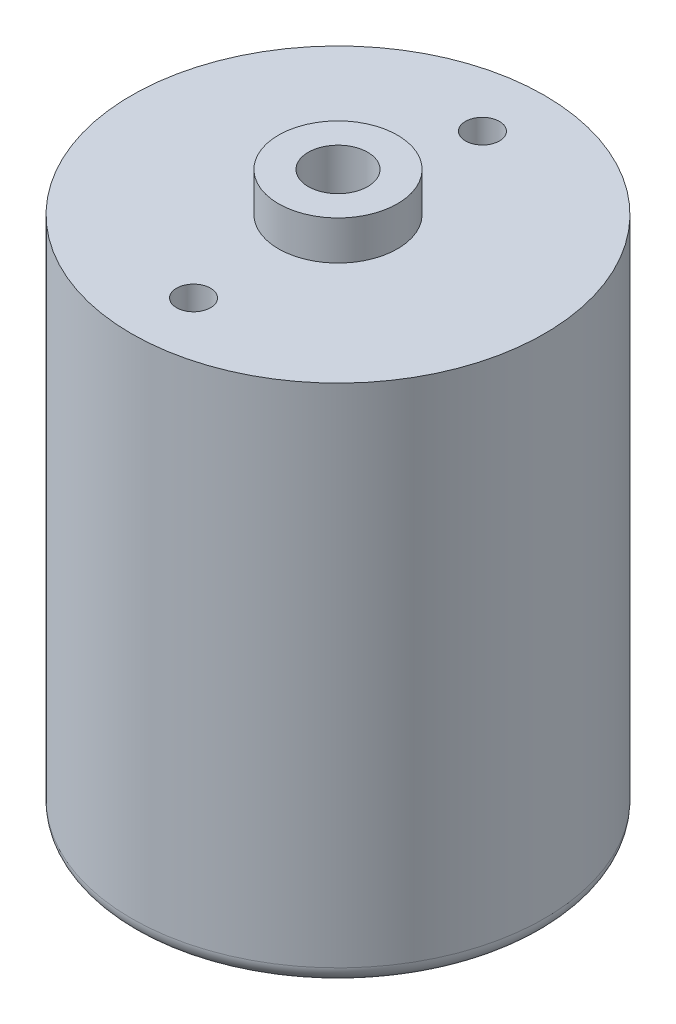
SolidWorks part; units mm, degrees
ref_plane "前视基准面" through (0, 0, 0) normal (0, 0, 1) x (1, 0, 0)
ref_plane "上视基准面" through (0, 0, 0) normal (0, 1, 0) x (1, 0, 0)
ref_plane "右视基准面" through (0, 0, 0) normal (1, 0, 0) x (0, 0, -1)
sketch "草图1" plane through (0, 0, 0) normal (0, 1, 0) x (1, 0, 0)
  circle A0 centre (0, 0) radius 12.15
  point P3 (0, 0)
  dimension "D1" = 24.3
extrude "凸台-拉伸1" add sketch "草图1" along normal blind 30.8
fillet "圆角1" radius 1 1 edges at (0, 0, 12.15)
sketch "草图2" plane through (0, 30.8, 0) normal (0, 1, 0) x (1, 0, 0)
  line L0 (0, 0) -> (-15.8805, 0) construction
  line L1 (-15.8805, 0) -> (22.8313, 0) construction
  line L2 (0, 0) -> (0, 12.7733) construction
  line L3 (0, 12.7733) -> (0, -13.3104) construction
  circle A0 centre (0, 8.5) radius 1
  circle A1 centre (0, -8.5) radius 1
  circle A2 centre (0, 0) radius 3.5
  dimension "D2" = 2
  dimension "D3" = 2
  dimension "D4" = 7
  dimension "D1" = 17
  dimension "D5" = 8.5
  dimension "D6" = 90
extrude "凸台-拉伸2" add sketch "草图2" along normal blind 2.3 and the other way blind 30.8 contours A2 | A1
sketch "草图3" plane through (0, 30.8, 0) normal (0, 1, 0) x (1, 0, 0)
  line L0 (-16.0799, 0) -> (21.4511, 0) construction
  line L1 (21.4511, 0) -> (0, 0) construction
  line L2 (0, 0) -> (0, 13.0419) construction
  line L3 (0, 13.0419) -> (0, -13.2433) construction
  circle A0 centre (0, 8.5) radius 1
  circle A1 centre (0, -8.5) radius 1
  dimension "D3" = 2
  dimension "D4" = 2
  dimension "D1" = 17
  dimension "D2" = 8.5
extrude "切除-拉伸1" cut sketch "草图3" against normal through all
sketch "草图4" plane through (0, 33.1, 0) normal (0, 1, 0) x (1, 0, 0)
  circle A0 centre (0, 0) radius 1.75
  dimension "D1" = 3.5
extrude "切除-拉伸2" cut sketch "草图4" against normal through all
